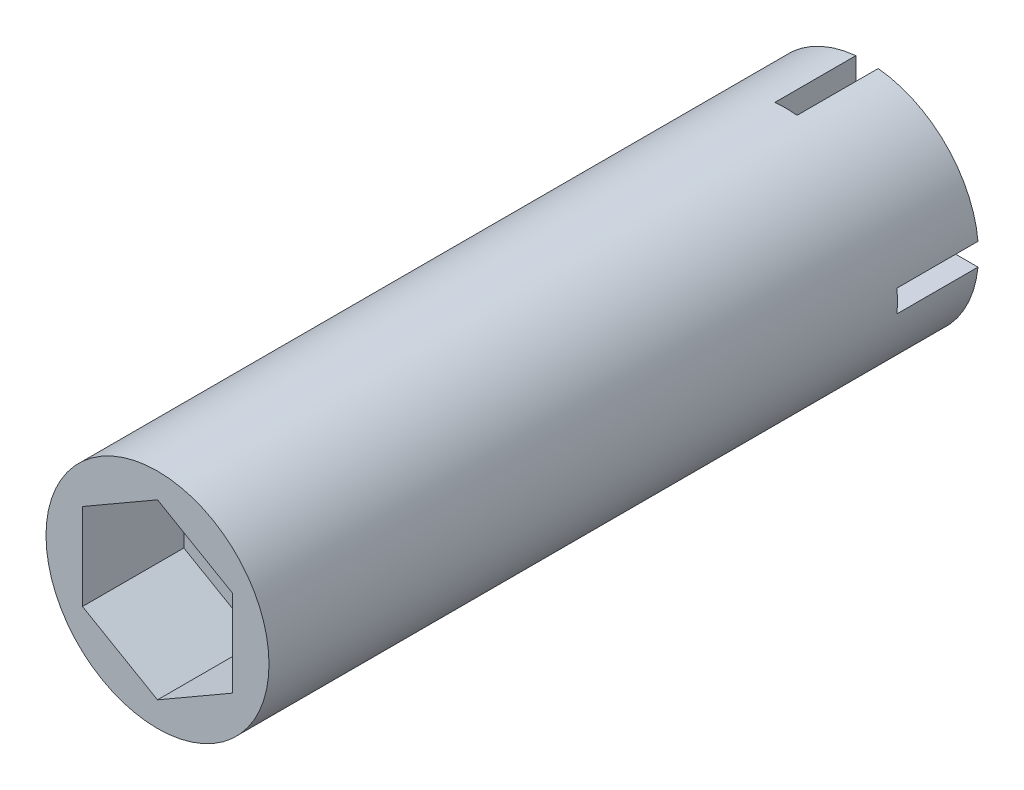
SolidWorks part; units mm, degrees
ref_plane "Plan de face" through (0, 0, 0) normal (0, 0, 1) x (1, 0, 0)
ref_plane "Plan de dessus" through (0, 0, 0) normal (0, 1, 0) x (1, 0, 0)
ref_plane "Plan de droite" through (0, 0, 0) normal (1, 0, 0) x (0, 0, -1)
sketch "Esquisse1" plane through (0, 0, 0) normal (0, 0, 1) x (1, 0, 0)
  circle A0 centre (0, 0) radius 5.5
  dimension "D1" = 11
extrude "Boss.-Extru.1" add sketch "Esquisse1" along normal blind 35
sketch "Esquisse2" plane through (0, 0, 35) normal (0, 0, 1) x (1, 0, 0)
  line L1 (0, -4.2724) -> (3.7, -2.1362)
  line L2 (3.7, -2.1362) -> (3.7, 2.1362)
  line L3 (3.7, 2.1362) -> (0, 4.2724)
  line L4 (0, 4.2724) -> (-3.7, 2.1362)
  line L5 (-3.7, 2.1362) -> (-3.7, -2.1362)
  line L6 (-3.7, -2.1362) -> (0, -4.2724)
  circle A0 centre (0, 0) radius 3.7 construction
  dimension "D1" = 7.4
extrude "Enlèv. mat.-Extru.1" cut sketch "Esquisse2" against normal blind 5
sketch "Esquisse3" plane through (0, 0, 30) normal (0, 0, 1) x (1, 0, 0)
  circle A0 centre (0, 0) radius 2.25
  circle A1 centre (0, 0) radius 5.5 construction
  dimension "D1" = 4.5
extrude "Enlèv. mat.-Extru.2" cut sketch "Esquisse3" against normal through all
sketch "Esquisse4" plane through (0, 0, 0) normal (0, 0, -1) x (-1, 0, 0)
  line L0 (-5.5, 0) -> (0, 0) construction
  line L1 (-0.55, 5.5) -> (0.55, 5.5)
  line L2 (-0.55, 5.5) -> (-0.55, 0.55)
  line L3 (-0.55, -5.5) -> (0.55, -5.5)
  line L4 (0.55, 5.5) -> (0.55, 0.55)
  line L5 (-5.5, 0.55) -> (-0.55, 0.55)
  line L6 (-5.5, 0.55) -> (-5.5, -0.55)
  line L7 (-5.5, -0.55) -> (-0.55, -0.55)
  line L8 (5.5, 0.55) -> (5.5, -0.55)
  line L9 (0, 5.5) -> (0, 0) construction
  line L10 (0.55, 0.55) -> (5.5, 0.55)
  line L11 (0.55, -0.55) -> (0.55, -5.5)
  line L12 (0.55, -0.55) -> (5.5, -0.55)
  line L13 (-0.55, -0.55) -> (-0.55, -5.5)
  circle A0 centre (0, 0) radius 5.5 construction
  dimension "D1" = 1.1
extrude "Enlèv. mat.-Extru.3" cut sketch "Esquisse4" against normal blind 4
